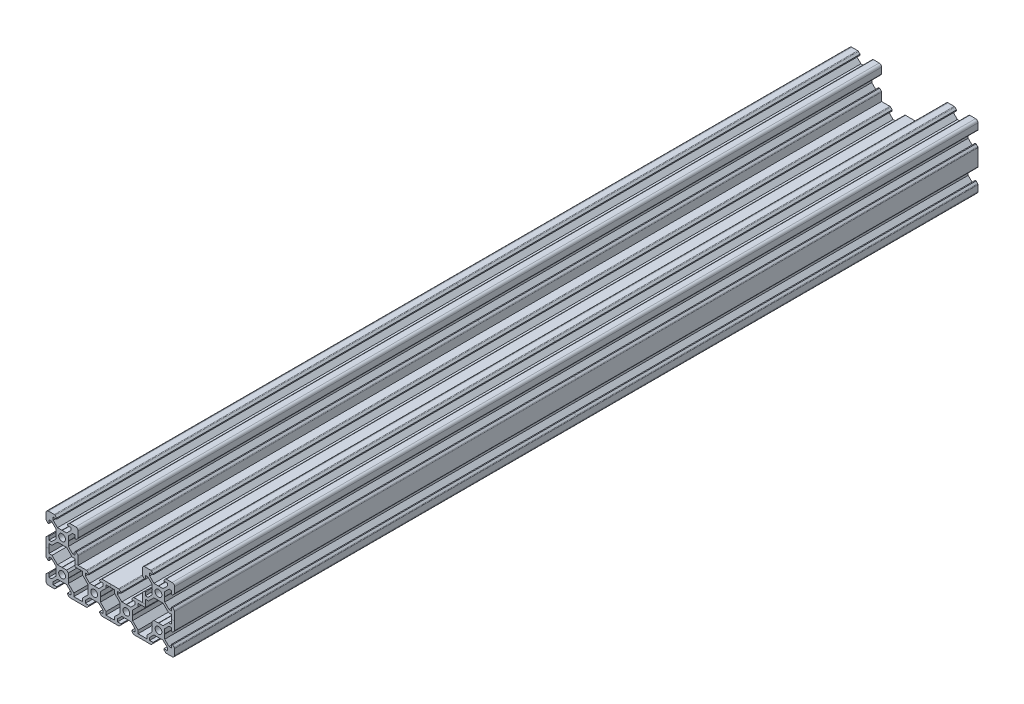
SolidWorks part; units mm, degrees
material "6063-T5"
ref_plane "Front" through (0, 0, 0) normal (0, 0, 1) x (1, 0, 0)
ref_plane "Top" through (0, 0, 0) normal (0, 1, 0) x (1, 0, 0)
ref_plane "Right" through (0, 0, 0) normal (1, 0, 0) x (0, 0, -1)
sketch "Sketch1" plane through (0, 0, 0) normal (0, 0, 1) x (1, 0, 0)
  line L0 (0, 32.3219) -> (0, -50.1713) construction
  line L1 (-2.8395, 3.9) -> (-0.1, 3.9)
  line L2 (-3.9, 2.8395) -> (-3.9, 0.1)
  line L3 (-2.8395, -3.9) -> (-0.1, -3.9)
  line L4 (3.9, 2.8395) -> (3.9, 0.1)
  line L5 (-29.7903, 0) -> (30, 0) construction
  line L6 (-0.1, -3.9) -> (0, -3.8)
  line L7 (-8.5, 10) -> (-4.8658, 10)
  line L8 (-10, 8.5) -> (-10, 4.8627)
  line L9 (-2.8395, -16.1) -> (-6.24, -12.6995)
  line L10 (10, 8.5) -> (10, 4.8627)
  line L11 (0, -3.8) -> (0.1, -3.9)
  line L12 (0.1, -3.9) -> (2.8395, -3.9)
  line L13 (-0.1, 3.9) -> (0, 3.8)
  line L14 (0, 3.8) -> (0.1, 3.9)
  line L15 (10, -10) -> (-10, 10) construction
  line L16 (-10, -10) -> (10, 10) construction
  line L17 (0.1, 3.9) -> (2.8395, 3.9)
  line L18 (-3.9, 0.1) -> (-3.8, 0)
  line L19 (-3.8, 0) -> (-3.9, -0.1)
  line L20 (-3.9, -0.1) -> (-3.9, -2.8395)
  line L21 (3.9, 0.1) -> (3.8, 0)
  line L22 (3.8, 0) -> (3.9, -0.1)
  line L23 (3.9, -0.1) -> (3.9, -2.8395)
  line L24 (0, -20) -> (58.4732, -20) construction
  line L25 (-3.9, 2.8395) -> (-6.561, 5.5005)
  line L26 (30, -50.1713) -> (30, 32.3219) construction
  line L27 (-5.5005, 8.2) -> (-3.3865, 8.2)
  line L28 (-8.2, 5.5005) -> (-8.2, 3.3865)
  line L29 (-10, -10) -> (-53.8942, -10) construction
  line L30 (8.2, 5.5005) -> (8.2, 3.3865)
  line L31 (-6.561, 5.5005) -> (-8.2, 5.5005)
  line L32 (-2.8395, 3.9) -> (-5.5005, 6.561)
  line L33 (-5.5005, 6.561) -> (-5.5005, 8.2)
  line L34 (6.561, 5.5005) -> (8.2, 5.5005)
  line L35 (3.9, 2.8395) -> (6.561, 5.5005)
  line L36 (5.5005, 6.561) -> (5.5005, 8.2)
  line L37 (2.8395, 3.9) -> (5.5005, 6.561)
  line L38 (6.561, -5.5005) -> (8.2, -5.5005)
  line L39 (-8.2, -12.6995) -> (-8.2, -7.3005)
  line L40 (2.8395, -3.9) -> (5.5005, -6.561)
  line L41 (3.9, -2.8395) -> (6.561, -5.5005)
  line L42 (-6.24, -12.6995) -> (-8.2, -12.6995)
  line L43 (-2.8395, -3.9) -> (-5.5005, -6.561)
  line L44 (-6.561, -5.5005) -> (-8.2, -5.5005)
  line L45 (-3.9, -2.8395) -> (-6.561, -5.5005)
  line L46 (30, -10) -> (10, -10) construction
  line L47 (-8.5, 10) -> (-10, 8.5) construction
  line L48 (8.5, 10) -> (10, 8.5) construction
  line L49 (-10, -10) -> (10, -30) construction
  line L50 (-5.5005, -6.561) -> (-6.24, -7.3005)
  line L51 (-3.9, -19.9) -> (-3.9, -17.1605)
  line L52 (-3.9, -17.1605) -> (-6.561, -14.4995)
  line L53 (10, 32.3219) -> (10, -50.1713) construction
  line L54 (-10, -30) -> (10, -10) construction
  line L55 (-4.3771, 9.7976) -> (-3.3865, 8.807)
  line L56 (-3.3865, 8.807) -> (-3.3865, 8.2)
  line L57 (4.3771, 9.7976) -> (3.3865, 8.807)
  line L58 (3.3865, 8.807) -> (3.3865, 8.2)
  line L59 (4.8658, 10) -> (8.5, 10)
  line L60 (3.3865, 8.2) -> (5.5005, 8.2)
  line L61 (-9.7968, 4.3732) -> (-8.807, 3.3865)
  line L62 (-8.807, 3.3865) -> (-8.2, 3.3865)
  line L63 (-9.7976, -4.3802) -> (-8.807, -3.3865)
  line L64 (-8.807, -3.3865) -> (-8.2, -3.3865)
  line L65 (9.7968, 4.3732) -> (8.807, 3.3865)
  line L66 (8.807, 3.3865) -> (8.2, 3.3865)
  line L67 (8.807, -3.3865) -> (8.2, -3.3865)
  line L68 (9.7976, -4.3802) -> (8.807, -3.3865)
  line L69 (-10, -4.87) -> (-10, -15.13)
  line L70 (-8.2, -3.3865) -> (-8.2, -5.5005)
  line L71 (10, -4.87) -> (10, -10)
  line L72 (8.2, -3.3865) -> (8.2, -5.5005)
  line L73 (-6.561, -14.4995) -> (-8.2, -14.4995)
  line L74 (-8.2, -16.6135) -> (-8.2, -14.4995)
  line L75 (-8.807, -16.6135) -> (-8.2, -16.6135)
  line L76 (-9.7976, -15.6198) -> (-8.807, -16.6135)
  line L77 (-10, -28.5) -> (-10, -24.8627)
  line L78 (-9.7968, -24.3732) -> (-8.807, -23.3865)
  line L79 (-8.807, -23.3865) -> (-8.2, -23.3865)
  line L80 (-8.2, -25.5005) -> (-8.2, -23.3865)
  line L81 (-6.561, -25.5005) -> (-8.2, -25.5005)
  line L82 (-3.9, -22.8395) -> (-6.561, -25.5005)
  line L83 (-3.9, -22.8395) -> (-3.9, -20.1)
  line L84 (-3.9, -20.1) -> (-3.8, -20)
  line L85 (-3.8, -20) -> (-3.9, -19.9)
  line L86 (0, -23.8) -> (0.1, -23.9)
  line L87 (-0.1, -23.9) -> (0, -23.8)
  line L88 (-2.8395, -23.9) -> (-0.1, -23.9)
  line L89 (0.1, -23.9) -> (2.8395, -23.9)
  line L90 (-2.8395, -23.9) -> (-5.5005, -26.561)
  line L91 (-5.5005, -28.2) -> (-3.3865, -28.2)
  line L92 (-5.5005, -26.561) -> (-5.5005, -28.2)
  line L93 (-4.3771, -29.7976) -> (-3.3865, -28.807)
  line L94 (-3.3865, -28.807) -> (-3.3865, -28.2)
  line L95 (-4.8658, -30) -> (-8.5, -30)
  line L96 (5.5005, -26.561) -> (5.5005, -28.2)
  line L97 (2.8395, -23.9) -> (5.5005, -26.561)
  line L98 (4.3771, -29.7976) -> (3.3865, -28.807)
  line L99 (3.3865, -28.807) -> (3.3865, -28.2)
  line L100 (3.3865, -28.2) -> (5.5005, -28.2)
  line L101 (4.8658, -30) -> (10, -30)
  line L102 (0.1, -16.1) -> (2.8395, -16.1)
  line L103 (0, -16.2) -> (0.1, -16.1)
  line L104 (-0.1, -16.1) -> (0, -16.2)
  line L105 (-2.8395, -16.1) -> (-0.1, -16.1)
  line L106 (3.9, -22.8395) -> (3.9, -20.1)
  line L107 (3.9, -20.1) -> (3.8, -20)
  line L108 (3.8, -20) -> (3.9, -19.9)
  line L109 (3.9, -19.9) -> (3.9, -17.1605)
  line L110 (3.9, -17.1605) -> (2.8395, -16.1)
  line L111 (-6.24, -7.3005) -> (-8.2, -7.3005)
  line L112 (6.24, -7.3005) -> (8.2, -7.3005)
  line L113 (5.5005, -6.561) -> (6.24, -7.3005)
  line L114 (12.6995, -28.2) -> (7.3005, -28.2)
  line L115 (7.3005, -28.2) -> (7.3005, -26.24)
  line L116 (7.3005, -26.24) -> (3.9, -22.8395)
  line L117 (16.1, -19.9) -> (16.1, -17.1605)
  line L118 (16.2, -20) -> (16.1, -19.9)
  line L119 (16.1, -20.1) -> (16.2, -20)
  line L120 (16.1, -22.8395) -> (16.1, -20.1)
  line L121 (20, -16.2) -> (19.9, -16.1)
  line L122 (20.1, -16.1) -> (20, -16.2)
  line L123 (22.8395, -16.1) -> (20.1, -16.1)
  line L124 (19.9, -16.1) -> (17.1605, -16.1)
  line L125 (23.9, -19.9) -> (23.9, -17.1605)
  line L126 (23.8, -20) -> (23.9, -19.9)
  line L127 (23.9, -20.1) -> (23.8, -20)
  line L128 (23.9, -22.8395) -> (23.9, -20.1)
  line L129 (20.1, -23.9) -> (20, -23.8)
  line L130 (22.8395, -23.9) -> (20.1, -23.9)
  line L131 (20, -23.8) -> (19.9, -23.9)
  line L132 (19.9, -23.9) -> (17.1605, -23.9)
  line L133 (12.6995, -28.2) -> (12.6995, -26.24)
  line L134 (14.4995, -26.561) -> (14.4995, -28.2)
  line L135 (17.1605, -23.9) -> (14.4995, -26.561)
  line L136 (12.6995, -26.24) -> (16.1, -22.8395)
  line L137 (16.6135, -28.807) -> (16.6135, -28.2)
  line L138 (16.6135, -28.2) -> (14.4995, -28.2)
  line L139 (15.6229, -29.7976) -> (16.6135, -28.807)
  line L140 (15.1342, -30) -> (10, -30)
  line L141 (20, 32.3219) -> (20, -50.1713) construction
  line L142 (10, -10) -> (30, -30) construction
  line L143 (30, -10) -> (10, -30) construction
  line L144 (27.3005, -28.2) -> (27.3005, -26.24)
  line L145 (25.5005, -26.561) -> (25.5005, -28.2)
  line L146 (24.3771, -29.7976) -> (23.3865, -28.807)
  line L147 (23.3865, -28.807) -> (23.3865, -28.2)
  line L148 (23.3865, -28.2) -> (25.5005, -28.2)
  line L149 (24.8658, -30) -> (30, -30)
  line L150 (27.3005, -28.2) -> (32.6995, -28.2)
  line L151 (25.5005, -26.561) -> (22.8395, -23.9)
  line L152 (27.3005, -26.24) -> (23.9, -22.8395)
  line L153 (25.5005, -13.439) -> (25.5005, -11.8)
  line L154 (27.3005, -11.8) -> (27.3005, -13.76)
  line L155 (27.3005, -13.76) -> (23.9, -17.1605)
  line L156 (25.5005, -13.439) -> (22.8395, -16.1)
  line L157 (12.6995, -11.8) -> (12.6995, -13.76)
  line L158 (14.4995, -13.439) -> (14.4995, -11.8)
  line L159 (17.1605, -16.1) -> (14.4995, -13.439)
  line L160 (16.1, -17.1605) -> (12.6995, -13.76)
  line L161 (23.3865, -11.193) -> (23.3865, -11.8)
  line L162 (16.6135, -11.193) -> (16.6135, -11.8)
  line L163 (16.6135, -11.8) -> (14.4995, -11.8)
  line L164 (23.3865, -11.8) -> (25.5005, -11.8)
  line L165 (15.6229, -10.2024) -> (16.6135, -11.193)
  line L166 (24.3771, -10.2024) -> (23.3865, -11.193)
  line L167 (24.8658, -10) -> (30, -10)
  line L168 (27.3005, -11.8) -> (32.6995, -11.8)
  line L169 (15.1342, -10) -> (10, -10)
  line L170 (12.6995, -11.8) -> (8.2, -11.8)
  line L171 (8.2, -11.8) -> (8.2, -7.3005)
  line L172 (60, -3.8) -> (59.9, -3.9)
  line L173 (60.1, -3.9) -> (60, -3.8)
  line L174 (63.8, 0) -> (63.9, -0.1)
  line L175 (63.9, 0.1) -> (63.8, 0)
  line L176 (56.1, 0.1) -> (56.2, 0)
  line L177 (56.2, 0) -> (56.1, -0.1)
  line L178 (60.1, 3.9) -> (60, 3.8)
  line L179 (60, 3.8) -> (59.9, 3.9)
  line L180 (62.8395, 3.9) -> (60.1, 3.9)
  line L181 (59.9, 3.9) -> (57.1605, 3.9)
  line L182 (63.9, 2.8395) -> (63.9, 0.1)
  line L183 (63.9, -0.1) -> (63.9, -2.8395)
  line L184 (62.8395, -3.9) -> (60.1, -3.9)
  line L185 (59.9, -3.9) -> (57.1605, -3.9)
  line L186 (56.1, -0.1) -> (56.1, -2.8395)
  line L187 (56.1, 2.8395) -> (56.1, 0.1)
  line L188 (60, -23.8) -> (59.9, -23.9)
  line L189 (60.1, -23.9) -> (60, -23.8)
  line L190 (60, -16.2) -> (59.9, -16.1)
  line L191 (60.1, -16.1) -> (60, -16.2)
  line L192 (63.8, -20) -> (63.9, -19.9)
  line L193 (63.9, -20.1) -> (63.8, -20)
  line L194 (56.2, -20) -> (56.1, -19.9)
  line L195 (56.1, -20.1) -> (56.2, -20)
  line L196 (40, -16.2) -> (40.1, -16.1)
  line L197 (39.9, -16.1) -> (40, -16.2)
  line L198 (36.2, -20) -> (36.1, -19.9)
  line L199 (36.1, -20.1) -> (36.2, -20)
  line L200 (43.8, -20) -> (43.9, -19.9)
  line L201 (43.9, -20.1) -> (43.8, -20)
  line L202 (40, -23.8) -> (40.1, -23.9)
  line L203 (39.9, -23.9) -> (40, -23.8)
  line L204 (56.1, -22.8395) -> (56.1, -20.1)
  line L205 (59.9, -23.9) -> (57.1605, -23.9)
  line L206 (62.8395, -23.9) -> (60.1, -23.9)
  line L207 (63.9, -22.8395) -> (63.9, -20.1)
  line L208 (63.9, -19.9) -> (63.9, -17.1605)
  line L209 (62.8395, -16.1) -> (60.1, -16.1)
  line L210 (59.9, -16.1) -> (57.1605, -16.1)
  line L211 (56.1, -19.9) -> (56.1, -17.1605)
  line L212 (43.9, -19.9) -> (43.9, -17.1605)
  line L213 (43.9, -22.8395) -> (43.9, -20.1)
  line L214 (40.1, -23.9) -> (42.8395, -23.9)
  line L215 (37.1605, -23.9) -> (39.9, -23.9)
  line L216 (36.1, -22.8395) -> (36.1, -20.1)
  line L217 (36.1, -19.9) -> (36.1, -17.1605)
  line L218 (37.1605, -16.1) -> (39.9, -16.1)
  line L219 (40.1, -16.1) -> (42.8395, -16.1)
  line L220 (42.8395, -23.9) -> (45.5005, -26.561)
  line L221 (47.3005, -26.24) -> (43.9, -22.8395)
  line L222 (43.9, -17.1605) -> (47.3005, -13.76)
  line L223 (42.8395, -16.1) -> (45.5005, -13.439)
  line L224 (34.4995, -13.439) -> (37.1605, -16.1)
  line L225 (32.6995, -13.76) -> (36.1, -17.1605)
  line L226 (34.4995, -26.561) -> (37.1605, -23.9)
  line L227 (32.6995, -26.24) -> (36.1, -22.8395)
  line L228 (47.3005, -11.8) -> (47.3005, -13.76)
  line L229 (45.5005, -13.439) -> (45.5005, -11.8)
  line L230 (47.3005, -28.2) -> (47.3005, -26.24)
  line L231 (45.5005, -26.561) -> (45.5005, -28.2)
  line L232 (34.4995, -26.561) -> (34.4995, -28.2)
  line L233 (32.6995, -28.2) -> (32.6995, -26.24)
  line L234 (34.4995, -13.439) -> (34.4995, -11.8)
  line L235 (32.6995, -11.8) -> (32.6995, -13.76)
  line L236 (43.3865, -28.2) -> (45.5005, -28.2)
  line L237 (43.3865, -28.807) -> (43.3865, -28.2)
  line L238 (44.3771, -29.7976) -> (43.3865, -28.807)
  line L239 (35.6229, -29.7976) -> (36.6135, -28.807)
  line L240 (36.6135, -28.807) -> (36.6135, -28.2)
  line L241 (36.6135, -28.2) -> (34.4995, -28.2)
  line L242 (44.3771, -10.2024) -> (43.3865, -11.193)
  line L243 (43.3865, -11.193) -> (43.3865, -11.8)
  line L244 (43.3865, -11.8) -> (45.5005, -11.8)
  line L245 (35.6229, -10.2024) -> (36.6135, -11.193)
  line L246 (36.6135, -11.193) -> (36.6135, -11.8)
  line L247 (36.6135, -11.8) -> (34.4995, -11.8)
  line L248 (35.1342, -30) -> (30, -30)
  line L249 (35.1342, -10) -> (30, -10)
  line L250 (51.8, -3.3865) -> (51.8, -5.5005)
  line L251 (51.193, -3.3865) -> (51.8, -3.3865)
  line L252 (50.2024, -4.3802) -> (51.193, -3.3865)
  line L253 (51.8, -11.8) -> (51.8, -7.3005)
  line L254 (50, -4.87) -> (50, -10)
  line L255 (44.8658, -10) -> (50, -10)
  line L256 (47.3005, -11.8) -> (51.8, -11.8)
  line L257 (62.8395, -16.1) -> (66.24, -12.6995)
  line L258 (63.9, -17.1605) -> (66.561, -14.4995)
  line L259 (63.9, -22.8395) -> (66.561, -25.5005)
  line L260 (62.8395, -23.9) -> (65.5005, -26.561)
  line L261 (57.1605, -23.9) -> (54.4995, -26.561)
  line L262 (52.6995, -26.24) -> (56.1, -22.8395)
  line L263 (63.9, 2.8395) -> (66.561, 5.5005)
  line L264 (62.8395, 3.9) -> (65.5005, 6.561)
  line L265 (57.1605, 3.9) -> (54.4995, 6.561)
  line L266 (56.1, 2.8395) -> (53.439, 5.5005)
  line L267 (63.9, -2.8395) -> (66.561, -5.5005)
  line L268 (62.8395, -3.9) -> (65.5005, -6.561)
  line L269 (57.1605, -3.9) -> (54.4995, -6.561)
  line L270 (56.1, -2.8395) -> (53.439, -5.5005)
  line L271 (64.3771, -29.7976) -> (63.3865, -28.807)
  line L272 (64.8658, -30) -> (68.5, -30)
  line L273 (65.5005, -28.2) -> (63.3865, -28.2)
  line L274 (55.6229, -29.7976) -> (56.6135, -28.807)
  line L275 (56.6135, -28.2) -> (54.4995, -28.2)
  line L276 (56.6135, -28.807) -> (56.6135, -28.2)
  line L277 (55.1342, -30) -> (50, -30)
  line L278 (44.8658, -30) -> (50, -30)
  line L279 (44.3771, -29.7976) -> (43.3865, -28.807)
  line L280 (43.3865, -28.807) -> (43.3865, -28.2)
  line L281 (43.3865, -28.2) -> (45.5005, -28.2)
  line L282 (47.3005, -28.2) -> (52.6995, -28.2)
  line L283 (70, -28.5) -> (70, -24.8627)
  line L284 (65.5005, -26.561) -> (65.5005, -28.2)
  line L285 (54.4995, -26.561) -> (54.4995, -28.2)
  line L286 (52.6995, -28.2) -> (52.6995, -26.24)
  line L287 (47.3005, -28.2) -> (47.3005, -26.24)
  line L288 (45.5005, -26.561) -> (45.5005, -28.2)
  line L289 (66.561, -5.5005) -> (68.2, -5.5005)
  line L290 (66.24, -7.3005) -> (68.2, -7.3005)
  line L291 (69.7976, -4.3802) -> (68.807, -3.3865)
  line L292 (68.807, -3.3865) -> (68.2, -3.3865)
  line L293 (68.2, -3.3865) -> (68.2, -5.5005)
  line L294 (68.2, -12.6995) -> (68.2, -7.3005)
  line L295 (70, -4.87) -> (70, -15.13)
  line L296 (69.7976, -15.6198) -> (68.807, -16.6135)
  line L297 (68.807, -16.6135) -> (68.2, -16.6135)
  line L298 (68.2, -16.6135) -> (68.2, -14.4995)
  line L299 (66.561, -14.4995) -> (68.2, -14.4995)
  line L300 (66.24, -12.6995) -> (68.2, -12.6995)
  line L301 (56.1, -17.1605) -> (57.1605, -16.1)
  line L302 (66.561, -25.5005) -> (68.2, -25.5005)
  line L303 (68.2, -25.5005) -> (68.2, -23.3865)
  line L304 (68.807, -23.3865) -> (68.2, -23.3865)
  line L305 (69.7968, -24.3732) -> (68.807, -23.3865)
  line L306 (53.76, -7.3005) -> (51.8, -7.3005)
  line L307 (53.439, -5.5005) -> (51.8, -5.5005)
  line L308 (54.4995, -6.561) -> (53.76, -7.3005)
  line L309 (65.5005, -6.561) -> (66.24, -7.3005)
  line L310 (54.4995, 6.561) -> (54.4995, 8.2)
  line L311 (56.6135, 8.2) -> (54.4995, 8.2)
  line L312 (56.6135, 8.807) -> (56.6135, 8.2)
  line L313 (55.6229, 9.7976) -> (56.6135, 8.807)
  line L314 (55.1342, 10) -> (51.5, 10)
  line L315 (50, 8.5) -> (50, 4.8627)
  line L316 (50.2032, 4.3732) -> (51.193, 3.3865)
  line L317 (51.193, 3.3865) -> (51.8, 3.3865)
  line L318 (51.8, 5.5005) -> (51.8, 3.3865)
  line L319 (53.439, 5.5005) -> (51.8, 5.5005)
  line L320 (66.561, 5.5005) -> (68.2, 5.5005)
  line L321 (68.2, 5.5005) -> (68.2, 3.3865)
  line L322 (68.807, 3.3865) -> (68.2, 3.3865)
  line L323 (69.7968, 4.3732) -> (68.807, 3.3865)
  line L324 (70, 8.5) -> (70, 4.8627)
  line L325 (68.5, 10) -> (64.8658, 10)
  line L326 (64.3771, 9.7976) -> (63.3865, 8.807)
  line L327 (63.3865, 8.807) -> (63.3865, 8.2)
  line L328 (65.5005, 8.2) -> (63.3865, 8.2)
  line L329 (65.5005, 6.561) -> (65.5005, 8.2)
  line L330 (63.3865, -28.807) -> (63.3865, -28.2)
  circle A0 centre (0, 0) radius 2.1
  circle A1 centre (0, -20) radius 2.1
  circle A2 centre (20, -20) radius 2.1
  circle A3 centre (60, 0) radius 2.1
  circle A4 centre (60, -20) radius 2.1
  circle A5 centre (40, -20) radius 2.1
  arc A6 (-8.5, 10) -> (-10, 8.5) centre (-8.5, 8.5) ccw
  arc A7 (10, 8.5) -> (8.5, 10) centre (8.5, 8.5) ccw
  arc A8 (-4.3771, 9.7976) -> (-4.8658, 10) centre (-4.8658, 9.3088) ccw
  arc A9 (4.3771, 9.7976) -> (4.8658, 10) centre (4.8658, 9.3088) cw
  arc A10 (-10, 4.8627) -> (-9.7968, 4.3732) centre (-9.3088, 4.8627) ccw
  arc A11 (9.7968, 4.3732) -> (10, 4.8627) centre (9.3088, 4.8627) ccw
  arc A12 (10, -4.87) -> (9.7976, -4.3802) centre (9.3062, -4.87) ccw
  arc A13 (-9.7976, -4.3802) -> (-10, -4.87) centre (-9.3062, -4.87) ccw
  arc A14 (-9.7976, -15.6198) -> (-10, -15.13) centre (-9.3062, -15.13) cw
  arc A15 (-8.5, -30) -> (-10, -28.5) centre (-8.5, -28.5) cw
  arc A16 (-10, -24.8627) -> (-9.7968, -24.3732) centre (-9.3088, -24.8627) cw
  arc A17 (-4.3771, -29.7976) -> (-4.8658, -30) centre (-4.8658, -29.3088) cw
  arc A18 (4.3771, -29.7976) -> (4.8658, -30) centre (4.8658, -29.3088) ccw
  arc A19 (15.6229, -29.7976) -> (15.1342, -30) centre (15.1342, -29.3088) cw
  arc A20 (24.3771, -29.7976) -> (24.8658, -30) centre (24.8658, -29.3088) ccw
  arc A21 (15.6229, -10.2024) -> (15.1342, -10) centre (15.1342, -10.6912) ccw
  arc A22 (24.3771, -10.2024) -> (24.8658, -10) centre (24.8658, -10.6912) cw
  arc A23 (44.3771, -29.7976) -> (44.8658, -30) centre (44.8658, -29.3088) ccw
  arc A24 (35.6229, -29.7976) -> (35.1342, -30) centre (35.1342, -29.3088) cw
  arc A25 (44.3771, -10.2024) -> (44.8658, -10) centre (44.8658, -10.6912) cw
  arc A26 (35.6229, -10.2024) -> (35.1342, -10) centre (35.1342, -10.6912) ccw
  arc A27 (50, -4.87) -> (50.2024, -4.3802) centre (50.6938, -4.87) cw
  arc A28 (64.3771, -29.7976) -> (64.8658, -30) centre (64.8658, -29.3088) ccw
  arc A29 (68.5, -30) -> (70, -28.5) centre (68.5, -28.5) ccw
  arc A30 (55.6229, -29.7976) -> (55.1342, -30) centre (55.1342, -29.3088) cw
  arc A31 (44.3771, -29.7976) -> (44.8658, -30) centre (44.8658, -29.3088) ccw
  arc A32 (69.7976, -4.3802) -> (70, -4.87) centre (69.3062, -4.87) cw
  arc A33 (69.7976, -15.6198) -> (70, -15.13) centre (69.3062, -15.13) ccw
  arc A34 (70, -24.8627) -> (69.7968, -24.3732) centre (69.3088, -24.8627) ccw
  arc A35 (55.6229, 9.7976) -> (55.1342, 10) centre (55.1342, 9.3088) ccw
  arc A36 (50, 8.5) -> (51.5, 10) centre (51.5, 8.5) cw
  arc A37 (50.2032, 4.3732) -> (50, 4.8627) centre (50.6912, 4.8627) cw
  arc A38 (70, 4.8627) -> (69.7968, 4.3732) centre (69.3088, 4.8627) cw
  arc A39 (68.5, 10) -> (70, 8.5) centre (68.5, 8.5) cw
  arc A40 (64.3771, 9.7976) -> (64.8658, 10) centre (64.8658, 9.3088) cw
  point P23 (-9.25, 9.25)
  point P69 (9.25, 9.25)
  point P188 (10, -28.2)
  point P223 (30, -28.2)
  point P320 (30, -11.8)
  dimension "D1" = 4.2
  dimension "D16" = 1.5
  dimension "D21" = 0.529
  dimension "D25" = 0.53
  dimension "D27" = 90
  dimension "D2" = 0.1
  dimension "D3" = 0.1
  dimension "D4" = 7.8
  dimension "D5" = 7.8
  dimension "D6" = 20
  dimension "D7" = 20
  dimension "D8" = 20
  dimension "D9" = 10
  dimension "D10" = 0.1
  dimension "D11" = 1.8
  dimension "D12" = 1.8
  dimension "D13" = 5.679
  dimension "D14" = 5.679
  dimension "D15" = 1.639
  dimension "D17" = 90
  dimension "D18" = 6.773
  dimension "D19" = 0.607
  dimension "D20" = 11.001
  dimension "D22" = 0.607
  dimension "D23" = 90
  dimension "D24" = 6.773
  dimension "D26" = 0.53
  dimension "D28" = 0.53
  dimension "D29" = 0.53
  dimension "D30" = 1.8
extrude "Boss-Extrude1" add sketch "Sketch1" along normal blind 500 contours A40 L326 L327 L328 L329 L264 L180 L178 L179 L181 L265 L310 L311 L312 L313 A35 L314 A36 L315 A37 L316 L317 L318 L319 L266 L187 L176 L177 L186 L270 L307 L250 L251 L252 A27 L254 L255 A25 L242 L243 L244 L229 L223 L219 L196 L197 L218 L224 L234 L247 L246
sketch "Sketch2" plane through (0, 0, 500) normal (0, 0, 1) x (1, 0, 0)
  line L0 (-10, -10) -> (70, -10)
  line L1 (-10, -4.87) -> (-10, -15.13) construction
  line L2 (70, -4.87) -> (70, -15.13) construction
split line "TopFixture1 - SplitLine"
sketch "Sketch3" plane through (0, 0, 0) normal (0, 0, -1) x (-1, 0, 0)
  line L0 (-70, -10) -> (10, -10)
  line L1 (-70, -4.87) -> (-70, -15.13) construction
  line L2 (10, -4.87) -> (10, -15.13) construction
split line "TopFixture2 - SplitLine"
sketch "Sketch6" plane through (0, 10, 0) normal (0, 1, 0) x (1, 0, 0)
  line L0 (-8.5, -250) -> (68.5, -250)
  line L1 (-8.5, -500) -> (-8.5, 0) construction
  line L2 (68.5, -500) -> (68.5, 0) construction
split line "TopFixture3 - SplitLine"
sketch "Sketch7" plane through (0, 0, 500) normal (0, 0, 1) x (1, 0, 0)
  line L0 (30, -30) -> (30, -10)
  line L1 (24.8658, -30) -> (35.1342, -30) construction
  line L2 (35.1342, -10) -> (24.8658, -10) construction
split line "SideFixture1 - SplitLine"
sketch "Sketch8" plane through (0, 0, 0) normal (0, 0, -1) x (-1, 0, 0)
  line L0 (-30, -10) -> (-30, -30)
  line L1 (-35.1342, -10) -> (-24.8658, -10) construction
  line L2 (-24.8658, -30) -> (-35.1342, -30) construction
split line "SideFixture2 - SplitLine"
sketch "Sketch9" plane through (-10, 0, 0) normal (-1, 0, 0) x (0, 0, 1)
  line L0 (250, -28.5) -> (250, 8.5)
  line L3 (500, -28.5) -> (0, -28.5) construction
  line L4 (500, 8.5) -> (0, 8.5) construction
split line "SideFixture3 - SplitLine"
equation "\"base-yheight\" = 500mm"
equation "\"D1@Boss-Extrude1\"=\"base-yheight\""
